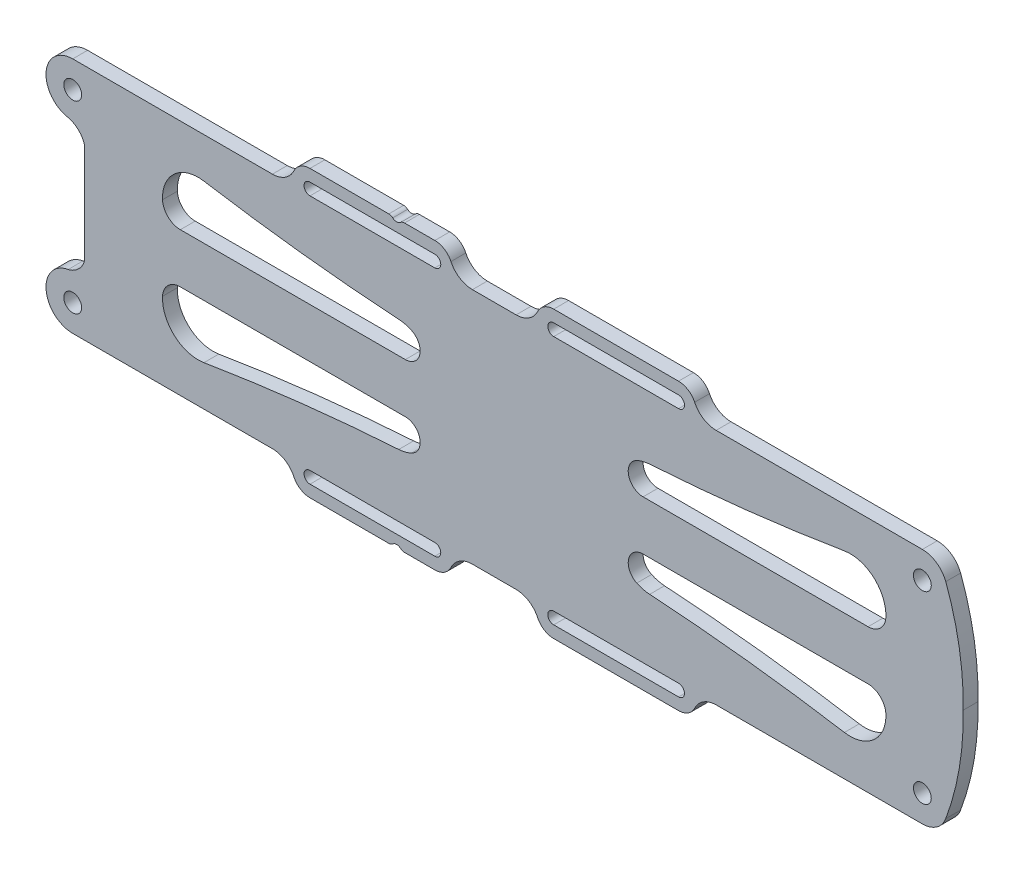
SolidWorks part; units mm, degrees
ref_plane "Alzado" through (0, 0, 0) normal (0, 0, 1) x (1, 0, 0)
ref_plane "Planta" through (0, 0, 0) normal (0, 1, 0) x (1, 0, 0)
ref_plane "Vista lateral" through (0, 0, 0) normal (1, 0, 0) x (0, 0, -1)
sketch "Croquis1" plane through (0, 0, 0) normal (0, 0, 1) x (1, 0, 0)
  line L0 (-1.7279, -20) -> (-35.3181, -20)
  line L1 (66.5967, 20) -> (45.5967, 20)
  line L2 (4.5967, 22) -> (25.5967, 22)
  line L3 (31.9212, 20) -> (39.2721, 20)
  line L4 (20.5008, 24) -> (25.5967, 24)
  line L5 (60.6296, -4.166) -> (98.4739, -4.166)
  line L6 (25.5967, -20) -> (4.5967, -20)
  line L7 (-33.3181, 0) -> (-33.3181, 8)
  line L8 (4.5967, 24) -> (17.855, 24)
  line L9 (66.5967, -20) -> (45.5967, -20)
  line L10 (4.5967, -22) -> (25.5967, -22)
  line L11 (20.6307, -4.166) -> (-17.2137, -4.166)
  line L12 (60.6296, 4.166) -> (98.4739, 4.166)
  line L13 (-33.3181, 0) -> (-33.3181, -8)
  line L14 (45.5967, -22) -> (66.5967, -22)
  line L15 (25.5967, 20) -> (4.5967, 20)
  line L16 (72.9212, 20) -> (107.6126, 20)
  line L17 (72.9212, -20) -> (107.6126, -20)
  line L18 (31.9212, -20) -> (39.2721, -20)
  line L19 (20.6307, 4.166) -> (-17.2137, 4.166)
  line L20 (20.5008, -24) -> (25.5967, -24)
  line L21 (45.5967, 24) -> (66.5967, 24)
  line L22 (4.5967, -24) -> (17.855, -24)
  line L23 (45.5967, -24) -> (66.5967, -24)
  line L24 (45.5967, 22) -> (66.5967, 22)
  line L25 (-1.7279, 20) -> (-35.3181, 20)
  arc A0 (42.8862, -22.2857) -> (39.2721, -20) centre (39.2721, -24) ccw
  arc A1 (72.9212, -20) -> (69.3072, -22.2857) centre (72.9212, -24) ccw
  arc A2 (19.8393, -23.75) -> (20.5008, -24) centre (20.5008, -23) ccw
  arc A3 (25.5967, -22) -> (25.5967, -20) centre (25.5967, -21) ccw
  arc A4 (94.5025, -13.2223) -> (61.7355, -9.4863) centre (40.5006, -341.2912) ccw
  arc A5 (60.6296, -4.166) -> (59.5659, -8.9284) centre (60.6296, -6.666) ccw
  arc A6 (59.5659, -8.9284) -> (61.7355, -9.4863) centre (62.1187, -3.4986) ccw
  arc A7 (107.6126, -20) -> (111.5451, -17.2675) centre (107.6126, -15.804) ccw
  arc A8 (111.5451, -17.2675) -> (114.474, 0) centre (67.8434, -0.9728) ccw
  arc A9 (19.5248, -9.4863) -> (-13.2422, -13.2223) centre (40.7597, -341.2912) ccw
  arc A10 (42.8862, -22.2857) -> (45.5967, -24) centre (45.5967, -21) ccw
  arc A11 (31.9212, -20) -> (28.3072, -22.2857) centre (31.9212, -24) ccw
  arc A12 (-13.2422, 13.2223) -> (19.5248, 9.4863) centre (40.7596, 341.2912) ccw
  arc A13 (1.8862, -22.2857) -> (4.5967, -24) centre (4.5967, -21) ccw
  circle A14 centre (107.6126, -15.5) radius 1.5
  arc A15 (66.5967, -22) -> (66.5967, -20) centre (66.5967, -21) ccw
  arc A16 (66.5967, -24) -> (69.3072, -22.2857) centre (66.5967, -21) ccw
  arc A17 (114.474, 0) -> (111.5451, 17.2675) centre (67.8434, 0.9728) ccw
  arc A18 (18.5165, 23.75) -> (17.855, 24) centre (17.855, 23) ccw
  arc A19 (45.5967, 22) -> (45.5967, 20) centre (45.5967, 21) ccw
  arc A20 (69.3072, 22.2857) -> (72.9212, 20) centre (72.9212, 24) ccw
  arc A21 (18.5165, 23.75) -> (19.8393, 23.75) centre (19.1779, 24.5) ccw
  circle A22 centre (-35.3181, -15.5) radius 1.5
  arc A23 (-1.7279, 20) -> (1.8862, 22.2857) centre (-1.7279, 24) ccw
  arc A24 (39.2721, 20) -> (42.8862, 22.2857) centre (39.2721, 24) ccw
  arc A25 (111.5451, 17.2675) -> (107.6126, 20) centre (107.6126, 15.804) ccw
  arc A26 (101.4708, 7.03) -> (94.5025, 13.2223) centre (95.477, 7.302) ccw
  arc A27 (19.5248, -9.4863) -> (21.6944, -8.9284) centre (19.1416, -3.4986) ccw
  arc A28 (61.7355, 9.4863) -> (59.5659, 8.9284) centre (62.1187, 3.4986) ccw
  arc A29 (4.5967, -20) -> (4.5967, -22) centre (4.5967, -21) ccw
  arc A30 (-35.3181, 20) -> (-36.0827, 11.0654) centre (-35.3181, 15.5) ccw
  arc A31 (25.5967, 20) -> (25.5967, 22) centre (25.5967, 21) ccw
  circle A32 centre (-35.3181, 15.5) radius 1.5
  circle A33 centre (107.6126, 15.5) radius 1.5
  arc A34 (101.4708, -7.03) -> (98.4739, -4.166) centre (98.4739, -7.166) ccw
  arc A35 (28.3072, 22.2857) -> (31.9212, 20) centre (31.9212, 24) ccw
  arc A36 (25.5967, -24) -> (28.3072, -22.2857) centre (25.5967, -21) ccw
  arc A37 (4.5967, 24) -> (1.8862, 22.2857) centre (4.5967, 21) ccw
  arc A38 (59.5659, 8.9284) -> (60.6296, 4.166) centre (60.6296, 6.666) ccw
  arc A39 (21.6944, -8.9284) -> (20.6307, -4.166) centre (20.6307, -6.666) ccw
  arc A40 (-13.2422, 13.2223) -> (-20.2106, 7.03) centre (-14.2167, 7.302) ccw
  arc A41 (-36.0827, -11.0654) -> (-35.3181, -20) centre (-35.3181, -15.5) ccw
  arc A42 (94.5025, -13.2223) -> (101.4708, -7.03) centre (95.477, -7.302) ccw
  arc A43 (45.5967, 24) -> (42.8862, 22.2857) centre (45.5967, 21) ccw
  arc A44 (20.6307, 4.166) -> (21.6944, 8.9284) centre (20.6307, 6.666) ccw
  arc A45 (17.855, -24) -> (18.5165, -23.75) centre (17.855, -23) ccw
  arc A46 (4.5967, 22) -> (4.5967, 20) centre (4.5967, 21) ccw
  arc A47 (20.5008, 24) -> (19.8393, 23.75) centre (20.5008, 23) ccw
  arc A48 (-20.2106, -7.03) -> (-13.2422, -13.2223) centre (-14.2167, -7.302) ccw
  arc A49 (1.8862, -22.2857) -> (-1.7279, -20) centre (-1.7279, -24) ccw
  arc A50 (-17.2137, -4.166) -> (-20.2106, -7.03) centre (-17.2137, -7.166) ccw
  arc A51 (-20.2106, 7.03) -> (-17.2137, 4.166) centre (-17.2136, 7.166) ccw
  arc A52 (98.4739, 4.166) -> (101.4708, 7.03) centre (98.4739, 7.166) ccw
  arc A53 (28.3072, 22.2857) -> (25.5967, 24) centre (25.5967, 21) ccw
  arc A54 (19.8393, -23.75) -> (18.5165, -23.75) centre (19.1779, -24.5) ccw
  arc A55 (66.5967, 20) -> (66.5967, 22) centre (66.5967, 21) ccw
  arc A56 (69.3072, 22.2857) -> (66.5967, 24) centre (66.5967, 21) ccw
  arc A57 (45.5967, -20) -> (45.5967, -22) centre (45.5967, -21) ccw
  arc A58 (61.7355, 9.4863) -> (94.5025, 13.2223) centre (40.5007, 341.2912) ccw
  arc A59 (21.6944, 8.9284) -> (19.5248, 9.4863) centre (19.1415, 3.4986) ccw
  spline S0 degree 3 poles (-36.0827, -11.0654) (-34.9682, -10.8733) (-33.3181, -9.5718) (-33.3181, -8) knots 0 0 0 0 1 1 1 1
  spline S1 degree 3 poles (-36.0827, 11.0654) (-34.9682, 10.8733) (-33.3181, 9.5718) (-33.3181, 8) knots 0 0 0 0 1 1 1 1
  point P3 (0, 0)
  point P4 (0, 0)
  point P5 (0, 0)
  point P6 (0, 0)
  point P7 (0, 0)
  point P8 (0, 0)
  point P9 (0, 0)
  point P10 (0, 0)
  point P11 (0, 0)
  point P12 (0, 0)
  point P13 (0, 0)
  point P14 (0, 0)
  point P15 (0, 0)
  point P16 (0, 0)
  point P17 (0, 0)
  point P18 (0, 0)
  point P19 (0, 0)
  point P20 (0, 0)
  point P21 (0, 0)
  point P22 (0, 0)
  point P23 (0, 0)
  point P24 (0, 0)
  point P25 (0, 0)
  point P26 (0, 0)
  point P27 (0, 0)
  point P28 (0, 0)
  point P29 (0, 0)
  point P30 (0, 0)
  point P31 (0, 0)
  point P32 (0, 0)
  point P33 (0, 0)
  point P34 (0, 0)
  point P35 (0, 0)
  point P36 (0, 0)
  point P37 (0, 0)
  point P38 (0, 0)
  point P39 (0, 0)
  point P40 (0, 0)
  point P41 (0, 0)
  point P42 (0, 0)
  point P43 (0, 0)
  point P44 (0, 0)
  point P45 (0, 0)
  point P46 (0, 0)
  point P47 (0, 0)
  point P48 (0, 0)
  point P49 (0, 0)
  point P50 (0, 0)
  point P51 (0, 0)
  point P52 (0, 0)
  point P53 (0, 0)
  point P54 (0, 0)
  point P55 (0, 0)
  point P56 (0, 0)
  point P57 (0, 0)
  point P58 (0, 0)
  point P59 (0, 0)
  point P60 (0, 0)
  point P61 (0, 0)
  point P62 (0, 0)
  point P63 (0, 0)
  point P64 (0, 0)
  point P65 (0, 0)
  point P66 (0, 0)
  point P67 (0, 0)
  point P68 (0, 0)
  point P69 (0, 0)
  point P70 (0, 0)
  point P71 (0, 0)
  point P72 (0, 0)
  point P73 (0, 0)
  point P74 (0, 0)
  point P75 (0, 0)
  point P76 (0, 0)
  point P77 (0, 0)
  point P78 (0, 0)
  point P79 (0, 0)
  point P80 (0, 0)
  point P81 (0, 0)
  point P82 (0, 0)
  point P83 (0, 0)
  point P84 (0, 0)
  point P85 (0, 0)
  point P86 (0, 0)
  point P87 (0, 0)
  point P88 (0, 0)
  point P89 (0, 0)
  point P90 (0, 0)
  point P91 (0, 0)
  point P92 (0, 0)
  point P93 (0, 0)
  point P94 (0, 0)
  point P95 (0, 0)
  point P96 (0, 0)
  point P97 (0, 0)
  point P98 (0, 0)
  point P99 (0, 0)
  point P100 (0, 0)
  point P101 (0, 0)
  point P102 (0, 0)
  point P103 (0, 0)
  point P104 (0, 0)
  point P105 (0, 0)
  point P106 (0, 0)
  point P107 (0, 0)
  point P108 (0, 0)
  point P109 (0, 0)
  point P110 (0, 0)
  point P111 (0, 0)
  point P112 (0, 0)
  point P113 (0, 0)
  point P114 (0, 0)
  point P115 (0, 0)
  point P116 (0, 0)
  point P117 (0, 0)
  point P118 (0, 0)
  point P119 (0, 0)
  point P120 (0, 0)
  point P121 (0, 0)
  point P122 (0, 0)
  point P123 (0, 0)
  point P124 (0, 0)
  point P125 (0, 0)
  point P126 (0, 0)
  point P127 (0, 0)
  point P128 (0, 0)
  point P129 (0, 0)
  point P130 (0, 0)
  point P131 (0, 0)
  point P132 (0, 0)
  point P133 (0, 0)
  point P134 (0, 0)
  point P135 (0, 0)
  point P136 (0, 0)
  point P137 (0, 0)
  point P138 (0, 0)
  point P139 (0, 0)
  point P140 (0, 0)
  point P141 (0, 0)
  point P142 (0, 0)
  point P143 (0, 0)
  point P144 (0, 0)
  point P145 (0, 0)
  point P146 (0, 0)
  point P147 (0, 0)
  point P148 (0, 0)
  point P149 (0, 0)
  point P150 (0, 0)
  point P151 (0, 0)
  point P152 (0, 0)
  point P153 (0, 0)
  point P154 (0, 0)
  point P155 (0, 0)
  point P156 (0, 0)
  point P157 (0, 0)
  point P158 (0, 0)
  point P159 (0, 0)
  point P160 (0, 0)
  point P161 (0, 0)
  point P162 (0, 0)
  point P163 (0, 0)
  point P164 (0, 0)
  point P165 (0, 0)
  point P166 (0, 0)
  point P167 (0, 0)
  point P168 (0, 0)
  point P169 (0, 0)
  point P170 (0, 0)
  point P171 (0, 0)
  point P172 (0, 0)
  point P173 (0, 0)
  point P174 (0, 0)
  point P175 (0, 0)
  point P176 (0, 0)
  point P177 (0, 0)
  point P178 (0, 0)
  point P179 (0, 0)
  point P180 (0, 0)
  point P181 (0, 0)
  point P182 (0, 0)
  point P183 (0, 0)
  point P184 (0, 0)
  point P185 (0, 0)
  point P186 (0, 0)
  point P187 (0, 0)
  point P188 (0, 0)
  point P189 (0, 0)
  point P190 (0, 0)
  point P191 (0, 0)
  point P192 (0, 0)
  point P193 (0, 0)
  point P194 (0, 0)
  point P195 (0, 0)
  point P196 (0, 0)
  point P197 (0, 0)
  point P198 (0, 0)
  point P199 (0, 0)
  point P200 (0, 0)
  point P201 (0, 0)
  point P202 (0, 0)
  point P203 (0, 0)
  point P204 (0, 0)
  point P205 (0, 0)
  point P206 (0, 0)
  point P207 (0, 0)
  point P208 (0, 0)
  point P209 (0, 0)
  point P210 (0, 0)
  point P211 (0, 0)
  point P212 (0, 0)
  point P213 (0, 0)
  point P214 (0, 0)
  point P215 (0, 0)
  point P216 (0, 0)
  point P217 (0, 0)
  point P218 (0, 0)
  point P219 (0, 0)
  point P220 (0, 0)
  point P221 (0, 0)
  point P222 (0, 0)
  point P223 (0, 0)
  point P224 (0, 0)
  point P225 (0, 0)
  point P226 (0, 0)
  point P227 (0, 0)
  point P228 (0, 0)
  point P229 (0, 0)
  point P230 (0, 0)
  point P231 (0, 0)
  point P232 (0, 0)
  point P233 (0, 0)
  point P234 (0, 0)
  point P235 (0, 0)
  point P236 (0, 0)
  point P237 (0, 0)
  point P238 (0, 0)
  point P239 (0, 0)
  point P240 (0, 0)
  point P241 (0, 0)
  point P242 (0, 0)
  point P243 (0, 0)
  point P244 (0, 0)
  point P245 (0, 0)
  point P246 (0, 0)
  point P247 (0, 0)
  point P248 (0, 0)
  point P249 (0, 0)
  point P250 (0, 0)
  point P251 (0, 0)
  point P252 (0, 0)
  point P253 (0, 0)
  point P254 (0, 0)
  point P255 (0, 0)
  point P256 (0, 0)
  point P257 (0, 0)
  point P258 (0, 0)
  point P259 (0, 0)
  point P260 (0, 0)
  point P261 (0, 0)
  point P262 (0, 0)
  point P263 (0, 0)
  point P264 (0, 0)
  point P265 (0, 0)
  point P266 (0, 0)
  point P267 (0, 0)
  point P268 (0, 0)
  point P269 (0, 0)
  point P270 (0, 0)
  point P271 (0, 0)
  point P272 (0, 0)
  point P273 (0, 0)
  point P274 (0, 0)
  point P275 (0, 0)
  point P276 (0, 0)
  point P277 (0, 0)
  point P278 (0, 0)
  point P279 (0, 0)
  point P280 (0, 0)
  point P281 (0, 0)
  point P282 (0, 0)
  point P283 (0, 0)
  point P284 (0, 0)
  point P285 (0, 0)
  point P286 (0, 0)
  point P287 (0, 0)
  point P288 (0, 0)
  point P289 (0, 0)
  point P290 (0, 0)
  point P291 (0, 0)
  point P292 (0, 0)
  point P293 (0, 0)
  point P294 (0, 0)
  point P295 (0, 0)
  point P296 (0, 0)
  point P297 (0, 0)
  point P298 (0, 0)
  point P299 (0, 0)
  point P300 (0, 0)
  point P301 (0, 0)
  point P302 (0, 0)
  point P303 (0, 0)
  point P304 (0, 0)
  point P305 (0, 0)
  point P306 (0, 0)
  point P307 (0, 0)
  point P308 (0, 0)
  point P309 (0, 0)
  point P310 (0, 0)
  point P311 (0, 0)
  point P312 (0, 0)
  point P313 (0, 0)
  point P314 (0, 0)
  point P315 (0, 0)
  point P316 (0, 0)
  point P317 (0, 0)
  point P318 (0, 0)
  point P319 (0, 0)
  point P320 (0, 0)
  point P321 (0, 0)
  point P322 (0, 0)
  point P323 (0, 0)
  point P324 (0, 0)
  point P325 (0, 0)
  point P326 (0, 0)
  point P327 (0, 0)
  point P328 (0, 0)
  point P329 (0, 0)
  point P330 (0, 0)
  point P331 (0, 0)
  point P332 (0, 0)
  point P333 (0, 0)
  point P334 (0, 0)
  point P335 (0, 0)
  point P336 (0, 0)
  point P337 (0, 0)
  point P338 (0, 0)
  point P339 (0, 0)
  point P340 (0, 0)
  point P341 (0, 0)
  point P342 (0, 0)
  point P343 (0, 0)
  point P344 (0, 0)
  point P345 (0, 0)
  point P346 (0, 0)
  point P347 (0, 0)
  point P348 (0, 0)
  point P349 (0, 0)
  point P350 (0, 0)
  point P351 (0, 0)
  point P352 (0, 0)
  point P353 (0, 0)
  point P354 (0, 0)
  point P355 (0, 0)
  point P356 (0, 0)
  point P357 (0, 0)
  point P358 (0, 0)
  point P359 (0, 0)
  point P360 (0, 0)
  point P361 (0, 0)
  point P362 (0, 0)
  point P363 (0, 0)
  point P364 (0, 0)
  point P365 (0, 0)
  point P366 (0, 0)
  point P367 (0, 0)
  point P368 (0, 0)
  point P369 (0, 0)
  point P370 (0, 0)
  point P371 (0, 0)
  point P372 (0, 0)
  point P373 (0, 0)
  point P374 (0, 0)
  point P375 (0, 0)
  point P376 (0, 0)
  point P377 (0, 0)
  point P378 (0, 0)
  point P379 (0, 0)
  point P380 (0, 0)
  point P381 (0, 0)
  point P382 (0, 0)
  point P383 (0, 0)
  point P384 (0, 0)
  point P385 (0, 0)
  point P386 (0, 0)
  point P387 (0, 0)
  point P388 (0, 0)
  point P389 (0, 0)
  point P390 (0, 0)
  point P391 (0, 0)
  point P392 (0, 0)
  point P393 (0, 0)
  point P394 (0, 0)
  point P395 (0, 0)
  point P396 (0, 0)
  point P397 (0, 0)
  point P398 (0, 0)
  point P399 (0, 0)
  point P400 (0, 0)
  point P401 (0, 0)
  point P402 (0, 0)
  point P403 (0, 0)
  point P404 (0, 0)
  point P405 (0, 0)
  point P406 (0, 0)
  point P407 (0, 0)
  point P408 (0, 0)
  point P409 (0, 0)
  point P410 (0, 0)
  point P411 (0, 0)
  point P412 (0, 0)
  point P413 (0, 0)
  point P414 (0, 0)
  point P415 (0, 0)
  point P416 (0, 0)
  point P417 (0, 0)
  point P418 (0, 0)
  point P419 (0, 0)
  point P420 (0, 0)
  point P421 (0, 0)
  point P422 (0, 0)
  point P423 (0, 0)
  point P424 (0, 0)
  point P425 (0, 0)
  point P426 (0, 0)
  point P427 (0, 0)
  point P428 (0, 0)
  point P429 (0, 0)
  point P430 (0, 0)
  point P431 (0, 0)
  point P432 (0, 0)
  point P433 (0, 0)
  point P434 (0, 0)
  point P435 (0, 0)
  point P436 (0, 0)
  point P437 (0, 0)
  point P438 (0, 0)
  point P439 (0, 0)
  point P440 (0, 0)
  point P441 (0, 0)
  point P442 (0, 0)
  point P443 (0, 0)
  point P444 (0, 0)
  point P445 (0, 0)
  point P446 (0, 0)
  point P447 (0, 0)
  point P448 (0, 0)
  point P449 (0, 0)
  point P450 (0, 0)
  point P451 (0, 0)
  point P452 (0, 0)
  point P453 (0, 0)
  point P454 (0, 0)
  point P455 (0, 0)
  point P456 (0, 0)
  point P457 (0, 0)
  point P458 (0, 0)
  point P459 (0, 0)
  point P460 (0, 0)
  point P461 (0, 0)
  point P462 (0, 0)
  point P463 (0, 0)
  point P464 (0, 0)
  point P465 (0, 0)
  point P466 (0, 0)
  point P467 (0, 0)
  point P468 (0, 0)
  point P469 (0, 0)
  point P470 (0, 0)
  point P471 (0, 0)
  point P472 (0, 0)
  point P473 (0, 0)
  point P474 (0, 0)
  point P475 (0, 0)
  point P476 (0, 0)
  point P477 (0, 0)
  point P478 (0, 0)
  point P479 (0, 0)
  point P480 (0, 0)
  point P481 (0, 0)
  point P482 (0, 0)
  point P483 (0, 0)
  point P484 (0, 0)
  point P485 (0, 0)
  point P486 (0, 0)
  point P487 (0, 0)
  point P488 (0, 0)
  point P489 (0, 0)
  point P490 (0, 0)
  point P491 (0, 0)
  point P492 (0, 0)
  point P493 (0, 0)
  point P494 (0, 0)
  point P495 (0, 0)
  point P496 (0, 0)
  point P497 (0, 0)
  point P498 (0, 0)
  point P499 (0, 0)
  point P500 (0, 0)
  point P501 (0, 0)
  point P502 (0, 0)
  point P503 (0, 0)
  point P504 (0, 0)
  point P505 (0, 0)
  point P506 (0, 0)
  point P507 (0, 0)
  point P508 (0, 0)
  point P509 (0, 0)
  point P510 (0, 0)
  point P511 (0, 0)
  point P512 (0, 0)
  point P513 (0, 0)
  point P514 (0, 0)
  point P515 (0, 0)
  point P516 (0, 0)
  point P517 (0, 0)
  point P518 (0, 0)
  point P519 (0, 0)
  point P520 (0, 0)
  point P521 (0, 0)
  point P522 (0, 0)
  point P523 (0, 0)
  point P524 (0, 0)
  point P525 (0, 0)
  point P526 (0, 0)
  point P527 (0, 0)
  point P528 (0, 0)
  point P529 (0, 0)
  point P530 (0, 0)
  point P531 (0, 0)
  point P532 (0, 0)
  point P533 (0, 0)
  point P534 (0, 0)
  point P535 (0, 0)
  point P536 (0, 0)
  point P537 (0, 0)
  point P538 (0, 0)
  point P539 (0, 0)
  point P540 (0, 0)
  point P541 (0, 0)
  point P542 (0, 0)
  point P543 (0, 0)
  point P544 (0, 0)
  point P545 (0, 0)
  point P546 (0, 0)
  point P547 (0, 0)
  point P548 (0, 0)
  point P549 (0, 0)
  point P550 (0, 0)
  point P551 (0, 0)
  point P552 (0, 0)
  point P553 (0, 0)
  point P554 (0, 0)
  point P555 (0, 0)
  point P556 (0, 0)
  point P557 (0, 0)
  point P558 (0, 0)
  point P559 (0, 0)
  point P560 (0, 0)
  point P561 (0, 0)
  point P562 (0, 0)
  point P563 (0, 0)
  point P564 (0, 0)
  point P565 (0, 0)
  point P566 (0, 0)
  point P567 (0, 0)
  point P568 (0, 0)
  point P569 (0, 0)
  point P570 (0, 0)
  point P571 (0, 0)
  point P572 (0, 0)
  point P573 (0, 0)
  point P574 (0, 0)
  point P575 (0, 0)
  point P576 (0, 0)
  point P577 (0, 0)
  point P578 (0, 0)
  point P579 (0, 0)
  point P580 (0, 0)
  point P581 (0, 0)
  point P582 (0, 0)
  point P583 (0, 0)
  point P584 (0, 0)
  point P585 (0, 0)
  point P586 (0, 0)
  point P587 (0, 0)
  point P588 (0, 0)
  point P589 (0, 0)
  point P590 (0, 0)
  point P591 (0, 0)
  point P592 (0, 0)
  point P593 (0, 0)
  point P594 (0, 0)
  point P595 (0, 0)
  point P596 (0, 0)
  point P597 (0, 0)
  point P598 (0, 0)
  point P599 (0, 0)
  point P600 (0, 0)
  point P601 (0, 0)
  point P602 (0, 0)
  point P603 (0, 0)
  point P604 (0, 0)
  point P605 (0, 0)
  point P606 (0, 0)
  point P607 (0, 0)
  point P608 (0, 0)
  point P609 (0, 0)
  point P610 (0, 0)
  point P611 (0, 0)
  point P612 (0, 0)
  point P613 (0, 0)
  point P614 (0, 0)
  point P615 (0, 0)
  point P616 (0, 0)
  point P617 (0, 0)
  point P618 (0, 0)
  point P619 (0, 0)
  point P620 (0, 0)
  point P621 (0, 0)
  point P622 (0, 0)
  point P623 (0, 0)
  point P624 (0, 0)
  point P625 (0, 0)
  point P626 (0, 0)
  point P627 (0, 0)
  point P628 (0, 0)
  point P629 (0, 0)
  point P630 (0, 0)
  point P631 (0, 0)
  point P632 (0, 0)
  point P633 (0, 0)
  point P634 (0, 0)
  point P635 (0, 0)
  point P636 (0, 0)
  point P637 (0, 0)
  point P638 (0, 0)
  point P639 (0, 0)
  point P640 (0, 0)
  point P641 (0, 0)
  point P642 (0, 0)
  point P643 (0, 0)
  point P644 (0, 0)
  point P645 (0, 0)
  point P646 (0, 0)
  point P647 (0, 0)
  point P648 (0, 0)
  point P649 (0, 0)
  point P650 (0, 0)
  point P651 (0, 0)
  point P652 (0, 0)
  point P653 (0, 0)
  point P654 (0, 0)
  point P655 (0, 0)
  point P656 (0, 0)
  point P657 (0, 0)
  point P658 (0, 0)
  point P659 (0, 0)
  point P660 (0, 0)
  point P661 (0, 0)
  point P662 (0, 0)
  point P663 (0, 0)
  point P664 (0, 0)
  point P665 (0, 0)
  point P666 (0, 0)
  point P667 (0, 0)
  point P668 (0, 0)
  point P669 (0, 0)
  point P670 (0, 0)
  point P671 (0, 0)
  point P672 (0, 0)
  point P673 (0, 0)
  point P674 (0, 0)
  point P675 (0, 0)
  point P676 (0, 0)
  point P677 (0, 0)
  point P678 (0, 0)
  point P679 (0, 0)
  point P680 (0, 0)
  point P681 (0, 0)
  point P682 (0, 0)
  point P683 (0, 0)
  point P684 (0, 0)
  point P685 (0, 0)
  point P686 (0, 0)
  point P687 (0, 0)
  point P688 (0, 0)
  point P689 (0, 0)
  point P690 (0, 0)
  point P691 (0, 0)
  point P692 (0, 0)
  point P693 (0, 0)
  point P694 (0, 0)
  point P695 (0, 0)
  point P696 (0, 0)
  point P697 (0, 0)
  point P698 (0, 0)
  point P699 (0, 0)
  point P700 (0, 0)
  point P701 (0, 0)
  point P702 (0, 0)
  point P703 (0, 0)
  point P704 (0, 0)
  point P705 (0, 0)
  point P706 (0, 0)
  point P707 (0, 0)
  point P708 (0, 0)
  point P709 (0, 0)
  point P710 (0, 0)
  point P711 (0, 0)
  point P712 (0, 0)
  point P713 (0, 0)
  point P714 (0, 0)
  point P715 (0, 0)
  point P716 (0, 0)
  point P717 (0, 0)
  point P718 (0, 0)
  point P719 (0, 0)
  point P720 (0, 0)
  point P721 (0, 0)
  point P722 (0, 0)
  point P723 (0, 0)
  point P724 (0, 0)
  point P725 (0, 0)
  point P726 (0, 0)
  point P727 (0, 0)
  point P728 (0, 0)
  point P729 (0, 0)
  point P730 (0, 0)
  point P731 (0, 0)
  point P732 (0, 0)
  point P733 (0, 0)
  point P734 (0, 0)
  point P735 (0, 0)
  point P736 (0, 0)
  point P737 (0, 0)
  point P738 (0, 0)
  point P739 (0, 0)
  point P740 (0, 0)
  point P741 (0, 0)
  point P742 (0, 0)
  point P743 (0, 0)
  point P744 (0, 0)
  point P745 (0, 0)
  point P746 (0, 0)
  point P747 (0, 0)
  point P748 (0, 0)
  point P749 (0, 0)
  point P750 (0, 0)
  point P751 (0, 0)
  point P752 (0, 0)
  point P753 (0, 0)
  point P754 (0, 0)
  point P755 (0, 0)
  point P756 (0, 0)
  point P757 (0, 0)
  point P758 (0, 0)
  point P759 (0, 0)
  point P760 (0, 0)
  point P761 (0, 0)
  point P762 (0, 0)
  point P763 (0, 0)
  point P764 (0, 0)
  point P765 (0, 0)
  point P766 (0, 0)
  point P767 (0, 0)
  point P768 (0, 0)
  point P769 (0, 0)
  point P770 (0, 0)
  point P771 (0, 0)
  point P772 (0, 0)
  point P773 (0, 0)
  point P774 (0, 0)
  point P775 (0, 0)
  point P776 (0, 0)
  point P777 (0, 0)
  point P778 (0, 0)
  point P779 (0, 0)
  point P780 (0, 0)
  point P781 (0, 0)
  point P782 (0, 0)
  point P783 (0, 0)
  point P784 (0, 0)
  point P785 (0, 0)
  point P786 (0, 0)
  point P787 (0, 0)
  point P788 (0, 0)
  point P789 (0, 0)
  point P790 (0, 0)
  point P791 (0, 0)
  point P792 (0, 0)
  point P793 (0, 0)
  point P794 (0, 0)
  point P795 (0, 0)
  point P796 (0, 0)
  point P797 (0, 0)
  point P798 (0, 0)
  point P799 (0, 0)
  point P800 (0, 0)
  point P801 (0, 0)
  point P802 (0, 0)
  point P803 (0, 0)
  point P804 (0, 0)
  point P805 (0, 0)
  point P806 (0, 0)
  point P807 (0, 0)
  point P808 (0, 0)
  point P809 (0, 0)
  point P810 (0, 0)
  point P811 (0, 0)
  point P812 (0, 0)
  point P813 (0, 0)
  point P814 (0, 0)
  point P815 (0, 0)
  point P816 (0, 0)
  point P817 (0, 0)
  point P818 (0, 0)
  point P819 (0, 0)
  point P820 (0, 0)
  point P821 (0, 0)
  point P822 (0, 0)
  point P823 (0, 0)
  point P824 (0, 0)
  point P825 (0, 0)
  point P826 (0, 0)
  point P827 (0, 0)
  point P828 (0, 0)
  point P829 (0, 0)
  point P830 (0, 0)
  point P831 (0, 0)
  point P832 (0, 0)
  point P833 (0, 0)
  point P834 (0, 0)
  point P835 (0, 0)
  point P836 (0, 0)
  point P837 (0, 0)
  point P838 (0, 0)
  point P839 (0, 0)
  point P840 (0, 0)
  point P841 (0, 0)
  point P842 (0, 0)
  point P843 (0, 0)
  point P844 (0, 0)
  point P845 (0, 0)
  point P846 (0, 0)
  point P847 (0, 0)
  point P848 (0, 0)
  point P849 (0, 0)
  point P850 (0, 0)
  point P851 (0, 0)
  point P852 (0, 0)
  point P853 (0, 0)
  point P854 (0, 0)
  point P855 (0, 0)
  point P856 (0, 0)
  point P857 (0, 0)
  point P858 (0, 0)
  point P859 (0, 0)
  point P860 (0, 0)
  point P861 (0, 0)
  point P862 (0, 0)
  point P863 (0, 0)
  point P864 (0, 0)
  point P865 (0, 0)
  point P866 (0, 0)
  point P867 (0, 0)
  point P868 (0, 0)
  point P869 (0, 0)
  point P870 (0, 0)
  point P871 (0, 0)
  point P872 (0, 0)
  point P873 (0, 0)
  point P874 (0, 0)
  point P875 (0, 0)
  point P876 (0, 0)
  point P877 (0, 0)
  point P878 (0, 0)
  point P879 (0, 0)
  point P880 (0, 0)
  point P881 (0, 0)
  point P882 (0, 0)
  point P883 (0, 0)
  point P884 (0, 0)
  point P885 (0, 0)
  point P886 (0, 0)
  point P887 (0, 0)
  point P888 (0, 0)
  point P889 (0, 0)
  point P890 (0, 0)
  point P891 (0, 0)
  point P892 (0, 0)
  point P893 (0, 0)
  point P894 (0, 0)
  point P895 (0, 0)
  point P896 (0, 0)
  point P897 (0, 0)
  point P898 (0, 0)
  point P899 (0, 0)
  point P900 (0, 0)
  point P901 (0, 0)
  point P902 (0, 0)
  point P903 (0, 0)
  point P904 (0, 0)
  point P905 (0, 0)
  point P906 (0, 0)
  point P907 (0, 0)
  point P908 (0, 0)
  point P909 (0, 0)
  point P910 (0, 0)
  point P911 (0, 0)
  point P912 (0, 0)
  point P913 (0, 0)
  point P914 (0, 0)
  point P915 (0, 0)
  point P916 (0, 0)
  point P917 (0, 0)
  point P918 (0, 0)
  point P919 (0, 0)
  point P920 (0, 0)
  point P921 (0, 0)
  point P922 (0, 0)
  point P923 (0, 0)
  point P924 (0, 0)
  point P925 (0, 0)
  point P926 (0, 0)
  point P927 (0, 0)
  point P928 (0, 0)
  point P929 (0, 0)
  point P930 (0, 0)
  point P931 (0, 0)
  point P932 (0, 0)
  point P933 (0, 0)
  point P934 (0, 0)
  point P935 (0, 0)
  point P936 (0, 0)
  point P937 (0, 0)
  point P938 (0, 0)
  point P939 (0, 0)
  point P940 (0, 0)
  point P941 (0, 0)
  point P942 (0, 0)
  point P943 (0, 0)
  point P944 (0, 0)
  point P945 (0, 0)
  point P946 (0, 0)
  point P947 (0, 0)
  point P948 (0, 0)
  point P949 (0, 0)
  point P950 (0, 0)
  point P951 (0, 0)
  point P952 (0, 0)
  point P953 (0, 0)
  point P954 (0, 0)
  point P955 (0, 0)
  point P956 (0, 0)
  point P957 (0, 0)
  point P958 (0, 0)
  point P959 (0, 0)
  point P960 (0, 0)
  point P961 (0, 0)
  point P962 (0, 0)
  point P963 (0, 0)
  point P964 (0, 0)
  point P965 (0, 0)
  point P966 (0, 0)
  point P967 (0, 0)
  point P968 (0, 0)
  point P969 (0, 0)
  point P970 (0, 0)
  point P971 (0, 0)
  point P972 (0, 0)
  point P973 (0, 0)
  point P974 (0, 0)
  point P975 (0, 0)
  point P976 (0, 0)
  point P977 (0, 0)
  point P978 (0, 0)
  point P979 (0, 0)
  point P980 (0, 0)
  point P981 (0, 0)
  point P982 (0, 0)
  point P983 (0, 0)
  point P984 (0, 0)
  point P985 (0, 0)
  point P986 (0, 0)
  point P987 (0, 0)
  point P988 (0, 0)
  point P989 (0, 0)
  point P990 (0, 0)
  point P991 (0, 0)
  point P992 (0, 0)
  point P993 (0, 0)
  point P994 (0, 0)
  point P995 (0, 0)
  point P996 (0, 0)
  point P997 (0, 0)
  point P998 (0, 0)
  point P999 (0, 0)
  point P1000 (0, 0)
  point P1001 (0, 0)
  point P1002 (0, 0)
  point P1003 (0, 0)
  point P1004 (0, 0)
  point P1005 (0, 0)
  point P1006 (0, 0)
  point P1007 (0, 0)
  point P1008 (0, 0)
  point P1009 (0, 0)
  point P1010 (0, 0)
  point P1011 (0, 0)
  point P1012 (0, 0)
  point P1013 (0, 0)
  point P1014 (0, 0)
  point P1015 (0, 0)
  point P1016 (0, 0)
  point P1017 (0, 0)
  point P1018 (0, 0)
  point P1019 (0, 0)
  point P1020 (0, 0)
  point P1021 (0, 0)
  point P1022 (0, 0)
  point P1023 (0, 0)
  point P1024 (0, 0)
  point P1025 (0, 0)
  point P1026 (0, 0)
  point P1027 (0, 0)
  point P1028 (0, 0)
  point P1029 (0, 0)
  point P1030 (0, 0)
  point P1031 (0, 0)
  point P1032 (0, 0)
  point P1033 (0, 0)
  point P1034 (0, 0)
  point P1035 (0, 0)
  point P1036 (0, 0)
  point P1037 (0, 0)
  point P1038 (0, 0)
  point P1039 (0, 0)
  point P1040 (0, 0)
  point P1041 (0, 0)
  point P1042 (0, 0)
  point P1043 (0, 0)
  point P1044 (0, 0)
  point P1045 (0, 0)
  point P1046 (0, 0)
  point P1047 (0, 0)
  point P1048 (0, 0)
  point P1049 (0, 0)
  point P1050 (0, 0)
  point P1051 (0, 0)
  point P1052 (0, 0)
  point P1053 (0, 0)
  point P1054 (0, 0)
  point P1055 (0, 0)
  point P1056 (0, 0)
  point P1057 (0, 0)
  point P1058 (0, 0)
  point P1059 (0, 0)
  point P1060 (0, 0)
  point P1061 (0, 0)
  point P1062 (0, 0)
  point P1063 (0, 0)
  point P1064 (0, 0)
  point P1065 (0, 0)
  point P1066 (0, 0)
  point P1067 (0, 0)
  point P1068 (0, 0)
  point P1069 (0, 0)
  point P1070 (0, 0)
  point P1071 (0, 0)
  point P1072 (0, 0)
  point P1073 (0, 0)
  point P1074 (0, 0)
  point P1075 (0, 0)
  point P1076 (0, 0)
  point P1077 (0, 0)
  point P1078 (0, 0)
  point P1079 (0, 0)
  point P1080 (0, 0)
  point P1081 (0, 0)
  point P1082 (0, 0)
  point P1083 (0, 0)
  point P1084 (0, 0)
  point P1085 (0, 0)
  point P1086 (0, 0)
  point P1087 (0, 0)
  point P1088 (0, 0)
  point P1089 (0, 0)
  point P1090 (0, 0)
  point P1091 (0, 0)
  point P1092 (0, 0)
  point P1093 (0, 0)
  point P1094 (0, 0)
  point P1095 (0, 0)
  point P1096 (0, 0)
  point P1097 (0, 0)
  point P1098 (0, 0)
  point P1099 (0, 0)
  point P1100 (0, 0)
  point P1101 (0, 0)
  point P1102 (0, 0)
  point P1103 (0, 0)
  point P1104 (0, 0)
  point P1105 (0, 0)
  point P1106 (0, 0)
  point P1107 (0, 0)
  point P1108 (0, 0)
  point P1109 (0, 0)
  point P1110 (0, 0)
  point P1111 (0, 0)
  point P1112 (0, 0)
  point P1113 (0, 0)
  point P1114 (0, 0)
  point P1115 (0, 0)
  point P1116 (0, 0)
  point P1117 (0, 0)
  point P1118 (0, 0)
  point P1119 (0, 0)
  point P1120 (0, 0)
  point P1121 (0, 0)
  point P1122 (0, 0)
  point P1123 (0, 0)
  point P1124 (0, 0)
  point P1125 (0, 0)
  point P1126 (0, 0)
  point P1127 (0, 0)
  point P1128 (0, 0)
  point P1129 (0, 0)
  point P1130 (0, 0)
  point P1131 (0, 0)
  point P1132 (0, 0)
  point P1133 (0, 0)
  point P1134 (0, 0)
  point P1135 (0, 0)
  point P1136 (0, 0)
  point P1137 (0, 0)
  point P1138 (0, 0)
  point P1139 (0, 0)
  point P1140 (0, 0)
  point P1141 (0, 0)
  point P1142 (0, 0)
  point P1143 (0, 0)
  point P1144 (0, 0)
  point P1145 (0, 0)
  point P1146 (0, 0)
  point P1147 (0, 0)
  point P1148 (0, 0)
  point P1149 (0, 0)
  point P1150 (0, 0)
  point P1151 (0, 0)
  point P1152 (0, 0)
  point P1153 (0, 0)
  point P1154 (0, 0)
  point P1155 (0, 0)
  point P1156 (0, 0)
  point P1157 (0, 0)
  point P1158 (0, 0)
  point P1159 (0, 0)
  point P1160 (0, 0)
  point P1161 (0, 0)
  point P1162 (0, 0)
  point P1163 (0, 0)
  point P1164 (0, 0)
  point P1165 (0, 0)
  point P1166 (0, 0)
  point P1167 (0, 0)
  point P1168 (0, 0)
  point P1169 (0, 0)
  point P1170 (0, 0)
  point P1171 (0, 0)
  point P1172 (0, 0)
  point P1173 (0, 0)
  point P1174 (0, 0)
  point P1175 (0, 0)
  point P1176 (0, 0)
  point P1177 (0, 0)
  point P1178 (0, 0)
  point P1179 (0, 0)
  point P1180 (0, 0)
  point P1181 (0, 0)
  point P1182 (0, 0)
  point P1183 (0, 0)
  point P1184 (0, 0)
  point P1185 (0, 0)
  point P1186 (0, 0)
  point P1187 (0, 0)
  point P1188 (0, 0)
  point P1189 (0, 0)
  point P1190 (0, 0)
  point P1191 (0, 0)
  point P1192 (0, 0)
  point P1193 (0, 0)
  point P1194 (0, 0)
  point P1195 (0, 0)
  point P1196 (0, 0)
  point P1197 (0, 0)
  point P1198 (0, 0)
  point P1199 (0, 0)
  point P1200 (0, 0)
  point P1201 (0, 0)
  point P1202 (0, 0)
  point P1203 (0, 0)
  point P1204 (0, 0)
  point P1205 (0, 0)
  point P1206 (0, 0)
  point P1207 (0, 0)
  point P1208 (0, 0)
  point P1209 (0, 0)
  point P1210 (0, 0)
  point P1211 (0, 0)
  point P1212 (0, 0)
  point P1213 (0, 0)
  point P1214 (0, 0)
  point P1215 (0, 0)
  point P1216 (0, 0)
  point P1217 (0, 0)
  point P1218 (0, 0)
  point P1219 (0, 0)
  point P1220 (0, 0)
  point P1221 (0, 0)
  point P1222 (0, 0)
  point P1223 (0, 0)
  point P1224 (0, 0)
  point P1225 (0, 0)
  point P1226 (0, 0)
  point P1227 (0, 0)
  point P1228 (0, 0)
  point P1229 (0, 0)
  point P1230 (0, 0)
  point P1231 (0, 0)
  point P1232 (0, 0)
  point P1233 (0, 0)
  point P1234 (0, 0)
  point P1235 (0, 0)
  point P1236 (0, 0)
  point P1237 (0, 0)
  point P1238 (0, 0)
  point P1239 (0, 0)
  point P1240 (0, 0)
  point P1241 (0, 0)
  point P1242 (0, 0)
  point P1243 (0, 0)
  point P1244 (0, 0)
  point P1245 (0, 0)
  point P1246 (0, 0)
  point P1247 (0, 0)
  point P1248 (0, 0)
  point P1249 (0, 0)
  point P1250 (0, 0)
  point P1251 (0, 0)
  point P1252 (0, 0)
  point P1253 (0, 0)
  point P1254 (0, 0)
  point P1255 (0, 0)
  point P1256 (0, 0)
  point P1257 (0, 0)
  point P1258 (0, 0)
  point P1259 (0, 0)
  point P1260 (0, 0)
  point P1261 (0, 0)
  point P1262 (0, 0)
  point P1263 (0, 0)
  point P1264 (0, 0)
  point P1265 (0, 0)
  point P1266 (0, 0)
  point P1267 (0, 0)
  point P1268 (0, 0)
  point P1269 (0, 0)
  point P1270 (0, 0)
  point P1271 (0, 0)
  point P1272 (0, 0)
  point P1273 (0, 0)
  point P1274 (0, 0)
  point P1275 (0, 0)
  point P1276 (0, 0)
  point P1277 (0, 0)
  point P1278 (0, 0)
  point P1279 (0, 0)
  point P1280 (0, 0)
  point P1281 (0, 0)
  point P1282 (0, 0)
  point P1283 (0, 0)
  point P1284 (0, 0)
  point P1285 (0, 0)
  point P1286 (0, 0)
  point P1287 (0, 0)
  point P1288 (0, 0)
  point P1289 (0, 0)
  point P1290 (0, 0)
  point P1291 (0, 0)
  point P1292 (0, 0)
  point P1293 (0, 0)
  point P1294 (0, 0)
  point P1295 (0, 0)
  point P1296 (0, 0)
  point P1297 (0, 0)
  point P1298 (0, 0)
  point P1299 (0, 0)
  point P1300 (0, 0)
  point P1301 (0, 0)
  point P1302 (0, 0)
  point P1303 (0, 0)
  point P1304 (0, 0)
  point P1305 (0, 0)
  point P1306 (0, 0)
  point P1307 (0, 0)
  point P1308 (0, 0)
  point P1309 (0, 0)
  point P1310 (0, 0)
  point P1311 (0, 0)
  point P1312 (0, 0)
  point P1313 (0, 0)
  point P1314 (0, 0)
  point P1315 (0, 0)
  point P1316 (0, 0)
  point P1317 (0, 0)
  point P1318 (0, 0)
  point P1319 (0, 0)
  point P1320 (0, 0)
  point P1321 (0, 0)
  point P1322 (0, 0)
  point P1323 (0, 0)
  point P1324 (0, 0)
  point P1325 (0, 0)
  point P1326 (0, 0)
  point P1327 (0, 0)
  point P1328 (0, 0)
  point P1329 (0, 0)
  point P1330 (0, 0)
  point P1331 (0, 0)
  point P1332 (0, 0)
  point P1333 (0, 0)
  point P1334 (0, 0)
  point P1335 (0, 0)
  point P1336 (0, 0)
  point P1337 (0, 0)
  point P1338 (0, 0)
  point P1339 (0, 0)
  point P1340 (0, 0)
  point P1341 (0, 0)
  point P1342 (0, 0)
  point P1343 (0, 0)
  point P1344 (0, 0)
  point P1345 (0, 0)
  point P1346 (0, 0)
  point P1347 (0, 0)
  point P1348 (0, 0)
  point P1349 (0, 0)
  point P1350 (0, 0)
  point P1351 (0, 0)
  point P1352 (0, 0)
  point P1353 (0, 0)
  point P1354 (0, 0)
  point P1355 (0, 0)
  point P1356 (0, 0)
  point P1357 (0, 0)
  point P1358 (0, 0)
  point P1359 (0, 0)
  point P1360 (0, 0)
  point P1361 (0, 0)
  point P1362 (0, 0)
  point P1363 (0, 0)
  point P1364 (0, 0)
  point P1365 (0, 0)
  point P1366 (0, 0)
  point P1367 (0, 0)
  point P1368 (0, 0)
  point P1369 (0, 0)
  point P1370 (0, 0)
  point P1371 (0, 0)
  point P1372 (0, 0)
  point P1373 (0, 0)
  point P1374 (0, 0)
  point P1375 (0, 0)
  point P1376 (0, 0)
  point P1377 (0, 0)
  point P1378 (0, 0)
  point P1379 (0, 0)
  point P1380 (0, 0)
  point P1381 (0, 0)
  point P1382 (0, 0)
  point P1383 (0, 0)
  point P1384 (0, 0)
  point P1385 (0, 0)
  point P1386 (0, 0)
  point P1387 (0, 0)
  point P1388 (0, 0)
  point P1389 (0, 0)
  point P1390 (0, 0)
  point P1391 (0, 0)
  point P1392 (0, 0)
  point P1393 (0, 0)
  point P1394 (0, 0)
  point P1395 (0, 0)
  point P1396 (0, 0)
  point P1397 (0, 0)
  point P1398 (0, 0)
  point P1399 (0, 0)
  point P1400 (0, 0)
  point P1401 (0, 0)
  point P1402 (0, 0)
  point P1403 (0, 0)
  point P1404 (0, 0)
  point P1405 (0, 0)
  point P1406 (0, 0)
  point P1407 (0, 0)
  point P1408 (0, 0)
  point P1409 (0, 0)
  point P1410 (0, 0)
  point P1411 (0, 0)
  point P1412 (0, 0)
  point P1413 (0, 0)
  point P1414 (0, 0)
  point P1415 (0, 0)
  point P1416 (0, 0)
  point P1417 (0, 0)
  point P1418 (0, 0)
  point P1419 (0, 0)
  point P1420 (0, 0)
  point P1421 (0, 0)
  point P1422 (0, 0)
  point P1423 (0, 0)
  point P1424 (0, 0)
  point P1425 (0, 0)
  point P1426 (0, 0)
  point P1427 (0, 0)
  point P1428 (0, 0)
  point P1429 (0, 0)
  point P1430 (0, 0)
  point P1431 (0, 0)
  point P1432 (0, 0)
  point P1433 (0, 0)
  point P1434 (0, 0)
  point P1435 (0, 0)
  point P1436 (0, 0)
  point P1437 (0, 0)
  point P1438 (0, 0)
  point P1439 (0, 0)
  point P1440 (0, 0)
  point P1441 (0, 0)
  point P1442 (0, 0)
  point P1443 (0, 0)
  point P1444 (0, 0)
  point P1445 (0, 0)
  point P1446 (0, 0)
  point P1447 (0, 0)
  point P1448 (0, 0)
  point P1449 (0, 0)
  point P1450 (0, 0)
  point P1451 (0, 0)
  point P1452 (0, 0)
  point P1453 (0, 0)
  point P1454 (0, 0)
  point P1455 (0, 0)
  point P1456 (0, 0)
  point P1457 (0, 0)
  point P1458 (0, 0)
  point P1459 (0, 0)
  point P1460 (0, 0)
  point P1461 (0, 0)
  point P1462 (0, 0)
  point P1463 (0, 0)
  point P1464 (0, 0)
  point P1465 (0, 0)
  point P1466 (0, 0)
  point P1467 (0, 0)
  point P1468 (0, 0)
  point P1469 (0, 0)
  point P1470 (0, 0)
  point P1471 (0, 0)
  point P1472 (0, 0)
  point P1473 (0, 0)
  point P1474 (0, 0)
  point P1475 (0, 0)
  point P1476 (0, 0)
  point P1477 (0, 0)
extrude "Saliente-Extruir1" add sketch "Croquis1" along normal blind 2.5
